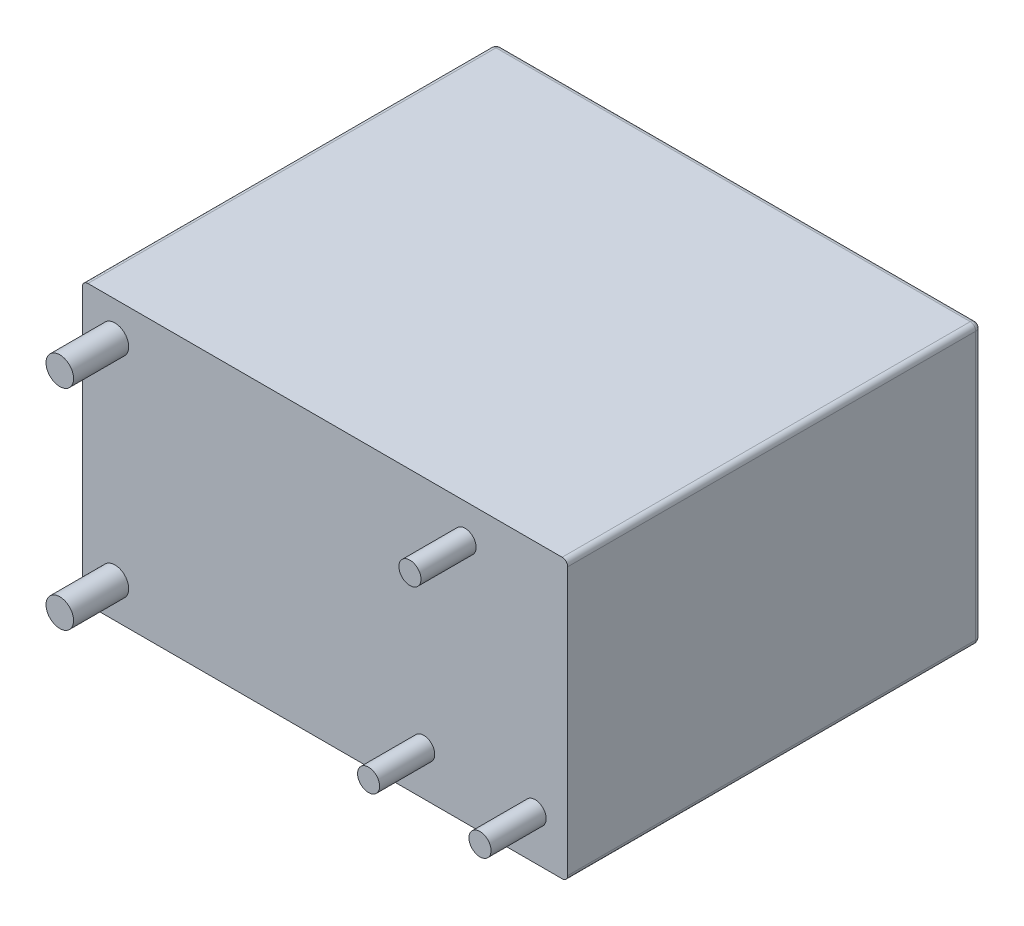
SolidWorks part; units mm, degrees
ref_plane "前视基准面" through (0, 0, 0) normal (0, 0, 1) x (1, 0, 0)
ref_plane "上视基准面" through (0, 0, 0) normal (0, 1, 0) x (1, 0, 0)
ref_plane "右视基准面" through (0, 0, 0) normal (1, 0, 0) x (0, 0, -1)
sketch "草图1" plane through (0, 0, 0) normal (0, 0, 1) x (1, 0, 0)
  line L1 (0, 0) -> (17.6, 0)
  line L2 (0, 0) -> (0, 10.1)
  line L3 (0, 10.1) -> (17.6, 10.1)
  line L4 (17.6, 0) -> (17.6, 10.1)
  dimension "D1" = 10.1
  dimension "D2" = 17.6
extrude "凸台-拉伸1" add sketch "草图1" against normal blind 15
sketch "草图2" plane through (0, 0, 0) normal (0, 0, 1) x (1, 0, 0)
  line L0 (0, 5.05) -> (17.6, 5.05) construction
  line L1 (0, 10.1) -> (0, 0) construction
  line L2 (17.6, 0) -> (17.6, 10.1) construction
  line L3 (8.8, 10.1) -> (8.8, 0) construction
  line L4 (17.6, 10.1) -> (0, 10.1) construction
  line L5 (0, 0) -> (17.6, 0) construction
  circle A0 centre (1.18, 8.85) radius 0.5
  circle A1 centre (13.88, 8.85) radius 0.4
  circle A2 centre (12.38, 1.597) radius 0.4
  circle A3 centre (16.42, 1.597) radius 0.4
  circle A4 centre (1.18, 1.25) radius 0.5
  dimension "D1" = 1
  dimension "D2" = 7.6
  dimension "D3" = 12.7
  dimension "D4" = 1.5
  dimension "D5" = 2.54
  dimension "D6" = 0.8
  dimension "D7" = 0.8
  dimension "D8" = 0.8
  dimension "D9" = 1.18
extrude "凸台-拉伸2" add sketch "草图2" along normal blind 2
fillet "圆角1" radius 0.2 8 edges at (17.6, 0, -7.5) (0, 0, -7.5) (8.8, 0, -15) (17.6, 5.05, -15) (0, 5.05, -15) (0, 10.1, -7.5) (17.6, 10.1, -7.5) (8.8, 10.1, -15)
sketch "草图3" plane through (0, 0, -15) normal (0, 0, -1) x (-1, 0, 0)
  line L0 (-17.4, 9.9) -> (-17.4, 0.2) construction
  line L1 (-17.4, 10.1) -> (-0.2, 10.1) construction
  circle A0 centre (-15.4, 8.1) radius 0.5
  dimension "D1" = 1
  dimension "D2" = 2
  dimension "D3" = 2
extrude "切除-拉伸1" cut sketch "草图3" against normal blind 0.5
